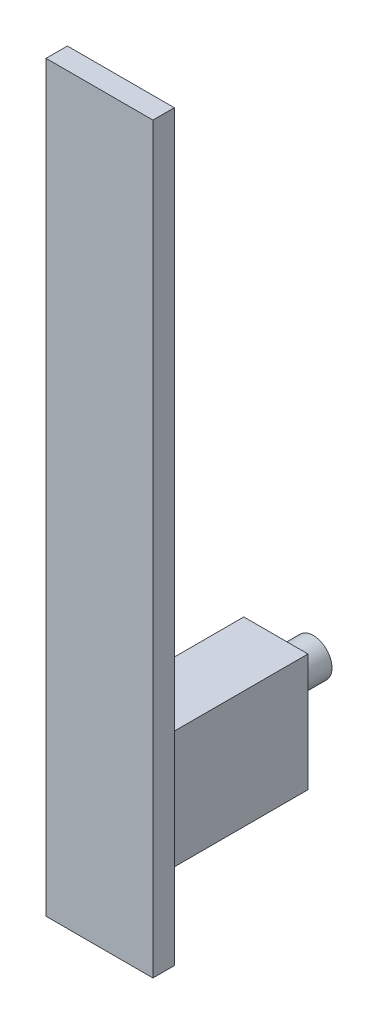
SolidWorks part; units mm, degrees
ref_plane "Ebene vorne" through (0, 0, 0) normal (0, 0, 1) x (1, 0, 0)
ref_plane "Ebene oben" through (0, 0, 0) normal (0, 1, 0) x (1, 0, 0)
ref_plane "Ebene rechts" through (0, 0, 0) normal (1, 0, 0) x (0, 0, -1)
sketch "Skizze1" plane through (0, 0, 0) normal (0, 0, 1) x (1, 0, 0)
  line L1 (0, 0) -> (20, 0)
  line L2 (0, 0) -> (0, 139)
  line L3 (0, 139) -> (20, 139)
  line L4 (20, 0) -> (20, 139)
  dimension "D1" = 139
  dimension "D2" = 20
extrude "Aufsatz-Linear austragen1" add sketch "Skizze1" along normal blind 4
sketch "Skizze7" plane through (0, 0, 0) normal (0, 0, -1) x (-1, 0, 0)
  line L0 (-20, 0) -> (-20, 139) construction
  line L1 (-20, 139) -> (0, 139) construction
  circle A0 centre (-10, 117) radius 3.5
  dimension "D1" = 7
  dimension "D2" = 10
  dimension "D3" = 22
extrude "Schnitt-Linear austragen1" cut sketch "Skizze7" against normal blind 3
sketch "Skizze8" plane through (0, 0, 0) normal (0, 0, -1) x (-1, 0, 0)
  line L0 (0, 0) -> (-20, 0) construction
  line L1 (-18, 45) -> (-2, 45)
  line L2 (-18, 45) -> (-18, 0)
  line L3 (-18, 0) -> (-2, 0)
  line L4 (-2, 45) -> (-2, 0)
  line L5 (-20, 0) -> (-20, 139) construction
  line L6 (0, 139) -> (0, 0) construction
  dimension "D1" = 0
  dimension "D2" = 2
  dimension "D3" = 2
  dimension "D4" = 45
extrude "Aufsatz-Linear austragen5" add sketch "Skizze8" along normal blind 2
sketch "Skizze9" plane through (0, 0, -2) normal (0, 0, -1) x (-1, 0, 0)
  line L0 (-18, 45) -> (-18, 0) construction
  line L1 (-16, 34) -> (-4, 34)
  line L2 (-16, 34) -> (-16, 12)
  line L3 (-16, 12) -> (-4, 12)
  line L4 (-4, 34) -> (-4, 12)
  line L5 (-18, 0) -> (-2, 0) construction
  dimension "D1" = 12
  dimension "D2" = 2
  dimension "D3" = 22
  dimension "D4" = 34
extrude "Aufsatz-Linear austragen6" add sketch "Skizze9" along normal blind 27
sketch "Skizze10" plane through (0, 0, -29) normal (0, 0, -1) x (-1, 0, 0)
  line L0 (-16, 34) -> (-16, 12) construction
  line L1 (-16, 12) -> (-4, 12) construction
  circle A0 centre (-10, 27) radius 3.5
  dimension "D1" = 7
  dimension "D2" = 6
  dimension "D3" = 15
extrude "Aufsatz-Linear austragen7" add sketch "Skizze10" along normal blind 7
